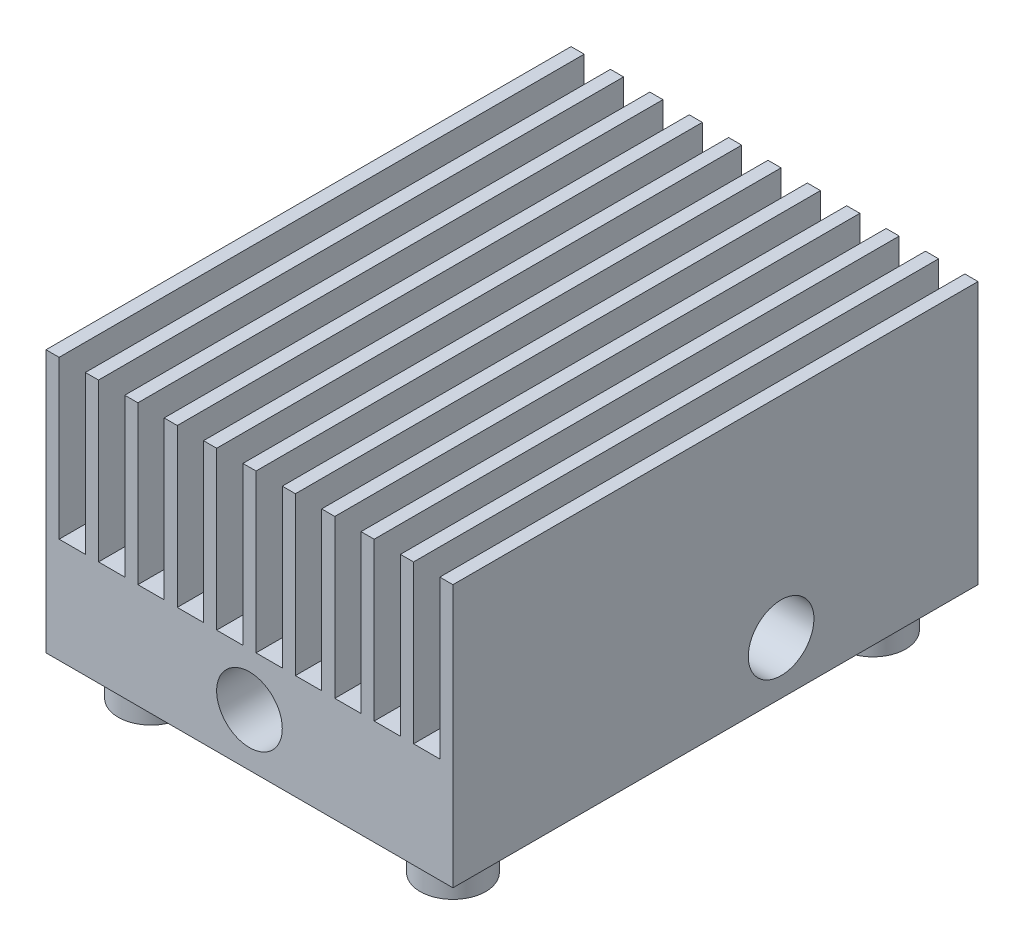
SolidWorks part; units mm, degrees
ref_plane "Front Plane" through (0, 0, 0) normal (0, 0, 1) x (1, 0, 0)
ref_plane "Top Plane" through (0, 0, 0) normal (0, 1, 0) x (1, 0, 0)
ref_plane "Right Plane" through (0, 0, 0) normal (1, 0, 0) x (0, 0, -1)
sketch "Sketch1" plane through (0, 0, 0) normal (0, 0, 1) x (1, 0, 0)
  line L0 (-15.5, 0) -> (-15.5, 20)
  line L1 (-14.5, 8) -> (-12.5, 8)
  line L2 (-12.5, 8) -> (-12.5, 20)
  line L3 (-15.5, 0) -> (15.5, 0)
  line L4 (15.5, 20) -> (15.5, 0)
  line L5 (-15.5, 20) -> (-14.5, 20)
  line L6 (-14.5, 20) -> (-14.5, 8)
  line L7 (-11.5, 8) -> (-9.5, 8)
  line L8 (-9.5, 8) -> (-9.5, 20)
  line L9 (-12.5, 20) -> (-11.5, 20)
  line L10 (-11.5, 20) -> (-11.5, 8)
  line L11 (-8.5, 8) -> (-6.5, 8)
  line L12 (-6.5, 8) -> (-6.5, 20)
  line L13 (-9.5, 20) -> (-8.5, 20)
  line L14 (-8.5, 20) -> (-8.5, 8)
  line L15 (-5.5, 8) -> (-3.5, 8)
  line L16 (-3.5, 8) -> (-3.5, 20)
  line L17 (-6.5, 20) -> (-5.5, 20)
  line L18 (-5.5, 20) -> (-5.5, 8)
  line L19 (-2.5, 8) -> (-0.5, 8)
  line L20 (-0.5, 8) -> (-0.5, 20)
  line L21 (-3.5, 20) -> (-2.5, 20)
  line L22 (-2.5, 20) -> (-2.5, 8)
  line L23 (0.5, 8) -> (2.5, 8)
  line L24 (2.5, 8) -> (2.5, 20)
  line L25 (-0.5, 20) -> (0.5, 20)
  line L26 (0.5, 20) -> (0.5, 8)
  line L27 (3.5, 8) -> (5.5, 8)
  line L28 (5.5, 8) -> (5.5, 20)
  line L29 (2.5, 20) -> (3.5, 20)
  line L30 (3.5, 20) -> (3.5, 8)
  line L31 (6.5, 8) -> (8.5, 8)
  line L32 (8.5, 8) -> (8.5, 20)
  line L33 (5.5, 20) -> (6.5, 20)
  line L34 (6.5, 20) -> (6.5, 8)
  line L35 (9.5, 8) -> (11.5, 8)
  line L36 (11.5, 8) -> (11.5, 20)
  line L37 (8.5, 20) -> (9.5, 20)
  line L38 (9.5, 20) -> (9.5, 8)
  line L39 (12.5, 8) -> (14.5, 8)
  line L40 (14.5, 8) -> (14.5, 20)
  line L41 (11.5, 20) -> (12.5, 20)
  line L42 (12.5, 20) -> (12.5, 8)
  line L43 (14.5, 20) -> (15.5, 20)
  point P4 (0, 0)
  dimension "D1" = 31
  dimension "D2" = 1
  dimension "D3" = 20
  dimension "D4" = 3
  dimension "D5" = 8
extrude "Extrude1" add sketch "Sketch1" against normal blind 40
sketch "Sketch2" plane through (0, 0, 0) normal (0, 0, 1) x (1, 0, 0)
  line L0 (-15.5, 0) -> (15.5, 0) construction
  circle A0 centre (0, 4) radius 2.5
  dimension "D2" = 5
  dimension "D1" = 4
extrude "Extrude2" cut sketch "Sketch2" against normal through all
sketch "Sketch3" plane through (15.5, 0, 0) normal (1, 0, 0) x (0, 0, -1)
  line L0 (40, 0) -> (0, 0) construction
  line L1 (40, 0) -> (40, 20) construction
  circle A0 centre (25, 4) radius 2.5
  dimension "D2" = 5
  dimension "D1" = 4
  dimension "D3" = 15
extrude "Extrude3" cut sketch "Sketch3" against normal through all
sketch "Sketch4" plane through (0, 0, 0) normal (0, -1, 0) x (1, 0, 0)
  line L0 (15.5, -40) -> (15.5, 0) construction
  line L1 (-15.5, 0) -> (15.5, 0) construction
  circle A0 centre (11.5, -4) radius 2.5
  circle A1 centre (11.5, -4) radius 1.5
  dimension "D1" = 5
  dimension "D4" = 3
  dimension "D2" = 4
  dimension "D3" = 4
extrude "Extrude4" add sketch "Sketch4" along normal blind 3
pattern_linear "LPattern6" count 2 spacing 23 along (-1, 0, 0) count 2 spacing 32 along (0, 0, -1) of "Extrude4"
